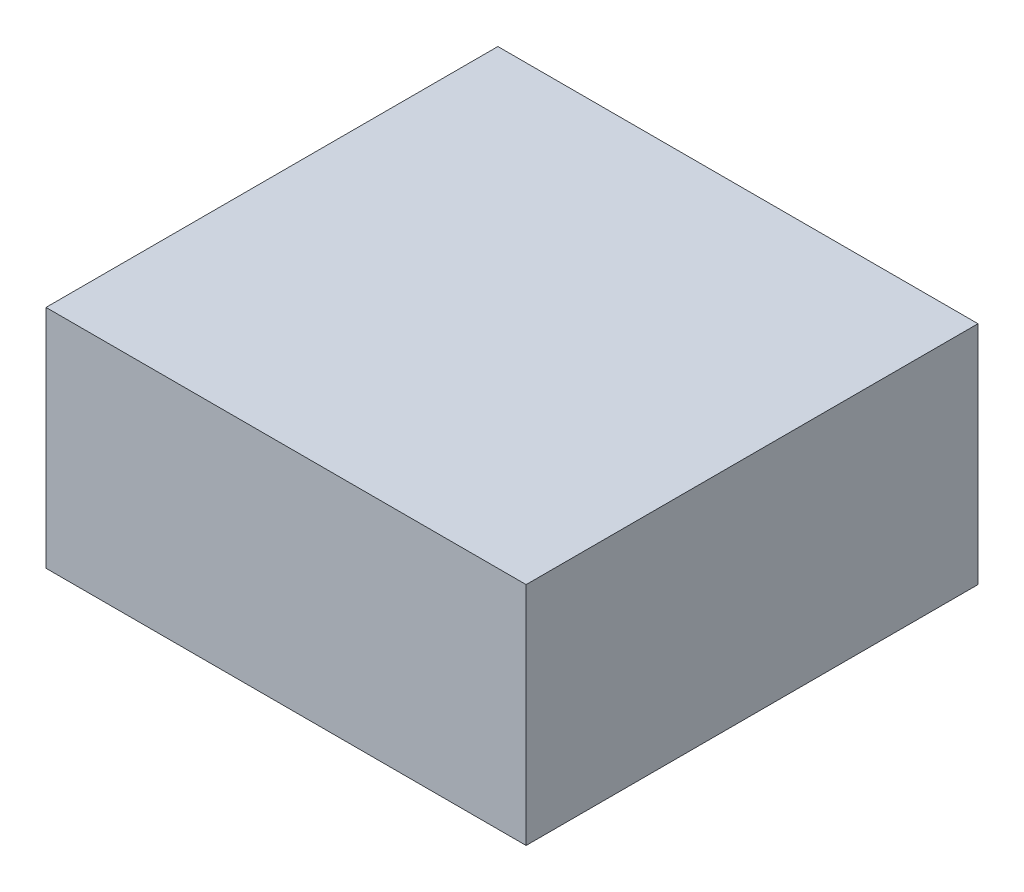
SolidWorks part; units mm, degrees
ref_plane "前视基准面" through (0, 0, 0) normal (0, 0, 1) x (1, 0, 0)
ref_plane "上视基准面" through (0, 0, 0) normal (0, 1, 0) x (1, 0, 0)
ref_plane "右视基准面" through (0, 0, 0) normal (1, 0, 0) x (0, 0, -1)
other "Configuration Table"
sketch "草图1" plane through (0, 0, 0) normal (0, 0, 1) x (1, 0, 0)
  line L1 (-42.5, -20) -> (42.5, -20)
  line L2 (-42.5, -20) -> (-42.5, 20)
  line L3 (-42.5, 20) -> (42.5, 20)
  line L4 (42.5, -20) -> (42.5, 20)
extrude "solid_obs_02_front_box" add sketch "草图1" along normal blind 80
